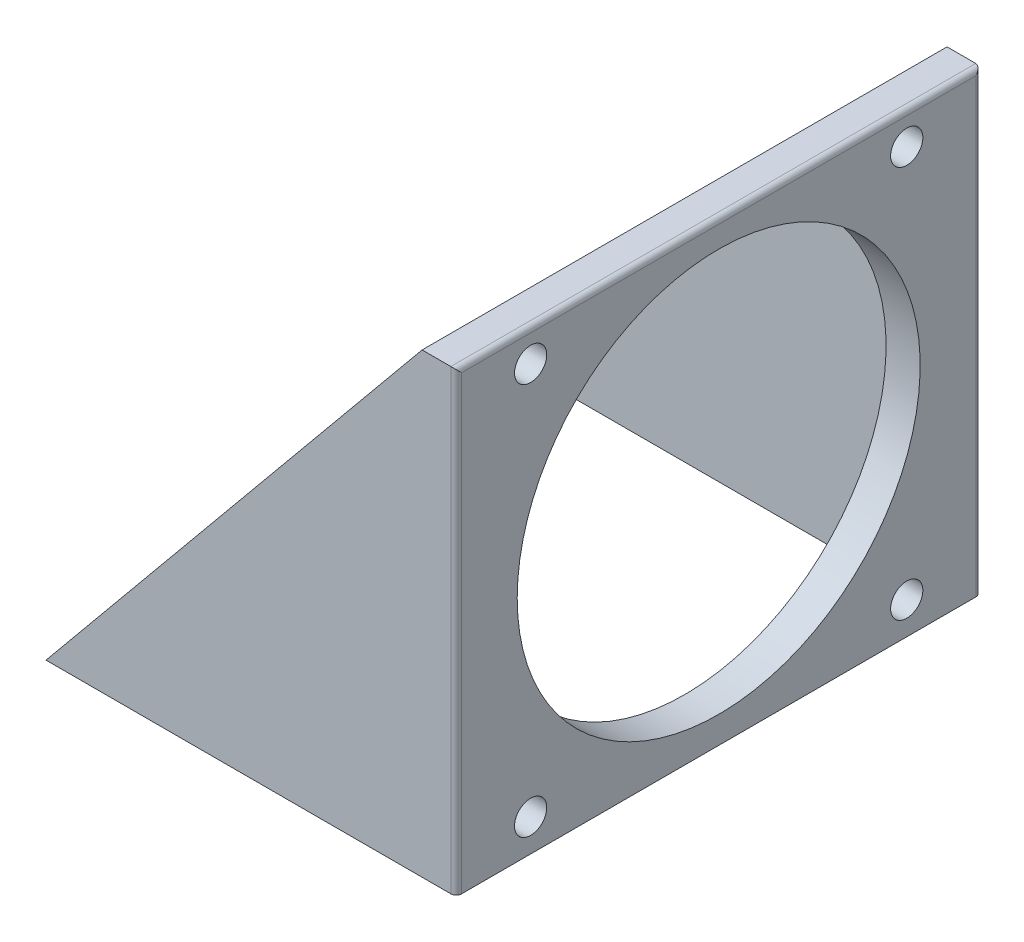
SolidWorks part; units mm, degrees
ref_plane "Alzado" through (0, 0, 0) normal (0, 0, 1) x (1, 0, 0)
ref_plane "Planta" through (0, 0, 0) normal (0, 1, 0) x (1, 0, 0)
ref_plane "Vista lateral" through (0, 0, 0) normal (1, 0, 0) x (0, 0, -1)
sketch "Croquis1" plane through (0, 0, 0) normal (0, 0, 1) x (1, 0, 0)
  line L0 (34.3074, -10.15) -> (4.3074, -10.15)
  line L1 (4.3074, -10.15) -> (4.3074, 68.5)
  line L2 (4.3074, 68.5) -> (-2.0426, 68.5)
  line L3 (-2.0426, 68.5) -> (-2.0426, -16.5)
  line L4 (-2.0426, -16.5) -> (34.3074, -16.5)
  line L5 (34.3074, -16.5) -> (34.3074, -10.15)
  dimension "D1" = 6.35
  dimension "D2" = 6.35
  dimension "D3" = 30
  dimension "D4" = 85
extrude "Saliente-Extruir1" add sketch "Croquis1" along normal blind 97.7
sketch "Croquis2" plane through (-2.0426, 0, 0) normal (-1, 0, 0) x (0, 0, 1)
  line L0 (97.7, -16.5) -> (0, -16.5) construction
  line L1 (0, 68.5) -> (6.35, 68.5)
  line L2 (0, 68.5) -> (0, -16.5)
  line L3 (0, -16.5) -> (6.35, -16.5)
  line L4 (6.35, 68.5) -> (6.35, -16.5)
  line L6 (97.7, 68.5) -> (91.35, 68.5)
  line L7 (97.7, 68.5) -> (97.7, -16.5)
  line L8 (97.7, -16.5) -> (91.35, -16.5)
  line L9 (91.35, 68.5) -> (91.35, -16.5)
  dimension "D1" = 6.35
  dimension "D2" = 6.35
extrude "Saliente-Extruir2" add sketch "Croquis2" along normal blind 70
sketch "Croquis3" plane through (0, 0, 97.7) normal (0, 0, 1) x (1, 0, 0)
  line L0 (-72.0426, -16.5) -> (-2.0426, -16.5) construction
  line L1 (-72.0426, -16.5) -> (34.3074, -16.5) construction
  line L2 (-2.0426, -16.5) -> (-2.0426, 68.5) construction
  line L3 (4.3074, 68.5) -> (-72.0426, 68.5) construction
  line L4 (-72.0426, -16.5) -> (-2.0426, 68.5)
  line L5 (-2.0426, 68.5) -> (-72.0426, 68.5)
  line L6 (-72.0426, 68.5) -> (-72.0426, -16.5)
  dimension "D1" = 70
extrude "Cortar-Extruir1" cut sketch "Croquis3" against normal blind 120
sketch "Croquis4" plane through (-2.0426, 0, 0) normal (-1, 0, 0) x (0, 0, 1)
  line L0 (6.35, 68.5) -> (91.35, -16.5) construction
  line L1 (6.35, 68.5) -> (6.35, 62.5) construction
  line L2 (6.35, -16.5) -> (6.35, 68.5) construction
  line L3 (6.35, 62.5) -> (13.85, 62.5) construction
  line L4 (6.35, -16.5) -> (13.85, -16.5) construction
  line L5 (91.35, -16.5) -> (6.35, -16.5) construction
  line L6 (13.85, -16.5) -> (13.85, -10.5) construction
  line L7 (48.85, 26) -> (48.85, -12.9732) construction
  circle A0 centre (48.85, 26) radius 37.5
  circle A1 centre (13.85, 62.5) radius 3
  circle A2 centre (13.85, -10.5) radius 3
  circle A3 centre (83.85, -10.5) radius 3
  circle A4 centre (83.85, 62.5) radius 3
  dimension "D1" = 75
  dimension "D4" = 6
  dimension "D7" = 6
  dimension "D2" = 6
  dimension "D3" = 7.5
  dimension "D5" = 6
  dimension "D6" = 7.5
extrude "Cortar-Extruir2" cut sketch "Croquis4" against normal blind 120
sketch "Croquis5" plane through (0, -10.15, 0) normal (0, 1, 0) x (1, 0, 0)
  line L0 (20.5577, -48.85) -> (20.5577, -18.85) construction
  line L1 (20.5577, -48.85) -> (20.5577, -78.85) construction
  line L2 (4.3074, -80.8705) -> (4.3074, -58.8213) construction
  line L3 (4.3074, -18.85) -> (34.3074, -18.85)
  line L4 (4.3074, -18.85) -> (4.3074, 0)
  line L5 (4.3074, 0) -> (34.3074, 0)
  line L6 (34.3074, -18.85) -> (34.3074, 0)
  line L7 (4.3074, -97.7) -> (4.3074, 0) construction
  line L8 (4.3074, -78.85) -> (34.3074, -78.85)
  line L9 (4.3074, -78.85) -> (4.3074, -97.7)
  line L10 (4.3074, -97.7) -> (34.3074, -97.7)
  line L11 (34.3074, -78.85) -> (34.3074, -97.7)
  dimension "D1" = 30
  dimension "D2" = 30
extrude "Cortar-Extruir3" cut sketch "Croquis5" against normal blind 120
fillet "Redondeo1" radius 1 5 edges at (4.3074, 68.5, 48.85) (4.3074, -13.325, 18.85) (4.3074, 26, 97.7) (4.3074, -13.325, 78.85) (4.3074, 26, 0)
sketch "Croquis6" plane through (0, 68.5, 0) normal (0, 1, 0) x (1, 0, 0)
  line L0 (4.3074, -1) -> (83.9211, -1)
  line L1 (83.9211, -1) -> (83.9211, -107.5012)
  line L2 (83.9211, -107.5012) -> (4.3074, -96.7)
  line L3 (4.3074, -96.7) -> (4.3074, -1)
extrude "Cortar-Extruir4" cut sketch "Croquis6" against normal blind 110
